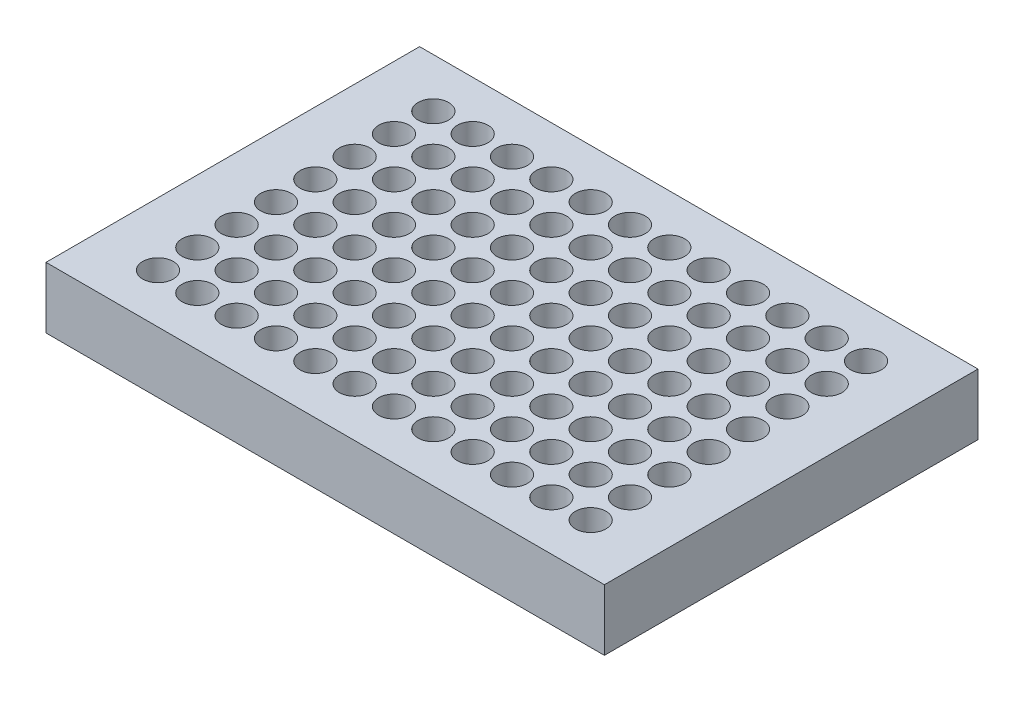
SolidWorks part; units mm, degrees
ref_plane "Front Plane" through (0, 0, 0) normal (0, 0, 1) x (1, 0, 0)
ref_plane "Top Plane" through (0, 0, 0) normal (0, 1, 0) x (1, 0, 0)
ref_plane "Right Plane" through (0, 0, 0) normal (1, 0, 0) x (0, 0, -1)
sketch "Sketch1" plane through (0, 0, 0) normal (0, 1, 0) x (1, 0, 0)
  line L0 (63.88, 85.48) -> (63.88, 0) construction
  line L1 (0, 0) -> (127.76, 0)
  line L2 (0, 0) -> (0, 85.48)
  line L3 (0, 85.48) -> (127.76, 85.48)
  line L4 (127.76, 0) -> (127.76, 85.48)
  line L5 (127.76, 42.74) -> (0, 42.74) construction
  circle A0 centre (59.38, 47.24) radius 3.5 construction
  circle A1 centre (14.38, 38.24) radius 3.5 construction
  circle A2 centre (23.38, 38.24) radius 3.5 construction
  circle A3 centre (32.38, 38.24) radius 3.5 construction
  circle A4 centre (50.38, 47.24) radius 3.5 construction
  circle A5 centre (41.38, 47.24) radius 3.5 construction
  circle A6 centre (32.38, 47.24) radius 3.5 construction
  circle A7 centre (23.38, 47.24) radius 3.5 construction
  circle A8 centre (14.38, 47.24) radius 3.5 construction
  circle A9 centre (41.38, 38.24) radius 3.5 construction
  circle A10 centre (50.38, 38.24) radius 3.5 construction
  circle A11 centre (59.38, 38.24) radius 3.5 construction
  circle A12 centre (68.38, 38.24) radius 3.5 construction
  circle A13 centre (77.38, 38.24) radius 3.5 construction
  circle A14 centre (86.38, 38.24) radius 3.5 construction
  circle A15 centre (113.38, 47.24) radius 3.5 construction
  circle A16 centre (104.38, 47.24) radius 3.5 construction
  circle A17 centre (95.38, 47.24) radius 3.5 construction
  circle A18 centre (86.38, 47.24) radius 3.5 construction
  circle A19 centre (77.38, 47.24) radius 3.5 construction
  circle A20 centre (95.38, 38.24) radius 3.5 construction
  circle A21 centre (104.38, 38.24) radius 3.5 construction
  circle A22 centre (113.38, 38.24) radius 3.5 construction
  circle A23 centre (68.38, 47.24) radius 3.5 construction
  circle A24 centre (59.38, 56.24) radius 3.5 construction
  circle A25 centre (50.38, 56.24) radius 3.5 construction
  circle A26 centre (41.38, 56.24) radius 3.5 construction
  circle A27 centre (32.38, 56.24) radius 3.5 construction
  circle A28 centre (23.38, 56.24) radius 3.5 construction
  circle A29 centre (14.38, 56.24) radius 3.5 construction
  circle A30 centre (113.38, 56.24) radius 3.5 construction
  circle A31 centre (104.38, 56.24) radius 3.5 construction
  circle A32 centre (95.38, 56.24) radius 3.5 construction
  circle A33 centre (86.38, 56.24) radius 3.5 construction
  circle A34 centre (77.38, 56.24) radius 3.5 construction
  circle A35 centre (68.38, 56.24) radius 3.5 construction
  circle A36 centre (59.38, 65.24) radius 3.5 construction
  circle A37 centre (50.38, 65.24) radius 3.5 construction
  circle A38 centre (41.38, 65.24) radius 3.5 construction
  circle A39 centre (32.38, 65.24) radius 3.5 construction
  circle A40 centre (23.38, 65.24) radius 3.5 construction
  circle A41 centre (14.38, 65.24) radius 3.5 construction
  circle A42 centre (113.38, 65.24) radius 3.5 construction
  circle A43 centre (104.38, 65.24) radius 3.5 construction
  circle A44 centre (95.38, 65.24) radius 3.5 construction
  circle A45 centre (86.38, 65.24) radius 3.5 construction
  circle A46 centre (77.38, 65.24) radius 3.5 construction
  circle A47 centre (68.38, 65.24) radius 3.5 construction
  circle A48 centre (59.38, 74.24) radius 3.5 construction
  circle A49 centre (50.38, 74.24) radius 3.5 construction
  circle A50 centre (41.38, 74.24) radius 3.5 construction
  circle A51 centre (32.38, 74.24) radius 3.5 construction
  circle A52 centre (23.38, 74.24) radius 3.5 construction
  circle A53 centre (14.38, 74.24) radius 3.5 construction
  circle A54 centre (113.38, 74.24) radius 3.5 construction
  circle A55 centre (104.38, 74.24) radius 3.5 construction
  circle A56 centre (95.38, 74.24) radius 3.5 construction
  circle A57 centre (86.38, 74.24) radius 3.5 construction
  circle A58 centre (77.38, 74.24) radius 3.5 construction
  circle A59 centre (68.38, 74.24) radius 3.5 construction
  circle A60 centre (14.38, 29.24) radius 3.5 construction
  circle A61 centre (23.38, 29.24) radius 3.5 construction
  circle A62 centre (32.38, 29.24) radius 3.5 construction
  circle A63 centre (41.38, 29.24) radius 3.5 construction
  circle A64 centre (50.38, 29.24) radius 3.5 construction
  circle A65 centre (59.38, 29.24) radius 3.5 construction
  circle A66 centre (68.38, 29.24) radius 3.5 construction
  circle A67 centre (77.38, 29.24) radius 3.5 construction
  circle A68 centre (86.38, 29.24) radius 3.5 construction
  circle A69 centre (95.38, 29.24) radius 3.5 construction
  circle A70 centre (104.38, 29.24) radius 3.5 construction
  circle A71 centre (113.38, 29.24) radius 3.5 construction
  circle A72 centre (14.38, 20.24) radius 3.5 construction
  circle A73 centre (23.38, 20.24) radius 3.5 construction
  circle A74 centre (32.38, 20.24) radius 3.5 construction
  circle A75 centre (41.38, 20.24) radius 3.5 construction
  circle A76 centre (50.38, 20.24) radius 3.5 construction
  circle A77 centre (59.38, 20.24) radius 3.5 construction
  circle A78 centre (68.38, 20.24) radius 3.5 construction
  circle A79 centre (77.38, 20.24) radius 3.5 construction
  circle A80 centre (86.38, 20.24) radius 3.5 construction
  circle A81 centre (95.38, 20.24) radius 3.5 construction
  circle A82 centre (104.38, 20.24) radius 3.5 construction
  circle A83 centre (113.38, 20.24) radius 3.5 construction
  circle A84 centre (14.38, 11.24) radius 3.5 construction
  circle A85 centre (23.38, 11.24) radius 3.5 construction
  circle A86 centre (32.38, 11.24) radius 3.5 construction
  circle A87 centre (41.38, 11.24) radius 3.5 construction
  circle A88 centre (50.38, 11.24) radius 3.5 construction
  circle A89 centre (59.38, 11.24) radius 3.5 construction
  circle A90 centre (68.38, 11.24) radius 3.5 construction
  circle A91 centre (77.38, 11.24) radius 3.5 construction
  circle A92 centre (86.38, 11.24) radius 3.5 construction
  circle A93 centre (95.38, 11.24) radius 3.5 construction
  circle A94 centre (104.38, 11.24) radius 3.5 construction
  circle A95 centre (113.38, 11.24) radius 3.5 construction
  dimension "D5" = 6
  dimension "D1" = 85.48
  dimension "D2" = 127.76
  dimension "D3" = 4
  dimension "D4" = 4
extrude "Boss-Extrude1" add sketch "Sketch1" along normal blind 14
sketch "Sketch6" plane through (0, 14, 0) normal (0, 1, 0) x (1, 0, 0)
  line L0 (63.88, 85.48) -> (63.88, 0) construction
  line L1 (0, 0) -> (127.76, 0) construction
  line L2 (0, 0) -> (0, 85.48) construction
  line L3 (0, 85.48) -> (127.76, 85.48) construction
  line L4 (127.76, 0) -> (127.76, 85.48) construction
  line L5 (127.76, 42.74) -> (0, 42.74) construction
  circle A0 centre (59.38, 47.24) radius 3.5
  circle A1 centre (14.38, 38.24) radius 3.5
  circle A2 centre (23.38, 38.24) radius 3.5
  circle A3 centre (32.38, 38.24) radius 3.5
  circle A4 centre (50.38, 47.24) radius 3.5
  circle A5 centre (41.38, 47.24) radius 3.5
  circle A6 centre (32.38, 47.24) radius 3.5
  circle A7 centre (23.38, 47.24) radius 3.5
  circle A8 centre (14.38, 47.24) radius 3.5
  circle A9 centre (41.38, 38.24) radius 3.5
  circle A10 centre (50.38, 38.24) radius 3.5
  circle A11 centre (59.38, 38.24) radius 3.5
  circle A12 centre (68.38, 38.24) radius 3.5
  circle A13 centre (77.38, 38.24) radius 3.5
  circle A14 centre (86.38, 38.24) radius 3.5
  circle A15 centre (113.38, 47.24) radius 3.5
  circle A16 centre (104.38, 47.24) radius 3.5
  circle A17 centre (95.38, 47.24) radius 3.5
  circle A18 centre (86.38, 47.24) radius 3.5
  circle A19 centre (77.38, 47.24) radius 3.5
  circle A20 centre (95.38, 38.24) radius 3.5
  circle A21 centre (104.38, 38.24) radius 3.5
  circle A22 centre (113.38, 38.24) radius 3.5
  circle A23 centre (68.38, 47.24) radius 3.5
  circle A24 centre (59.38, 56.24) radius 3.5
  circle A25 centre (50.38, 56.24) radius 3.5
  circle A26 centre (41.38, 56.24) radius 3.5
  circle A27 centre (32.38, 56.24) radius 3.5
  circle A28 centre (23.38, 56.24) radius 3.5
  circle A29 centre (14.38, 56.24) radius 3.5
  circle A30 centre (113.38, 56.24) radius 3.5
  circle A31 centre (104.38, 56.24) radius 3.5
  circle A32 centre (95.38, 56.24) radius 3.5
  circle A33 centre (86.38, 56.24) radius 3.5
  circle A34 centre (77.38, 56.24) radius 3.5
  circle A35 centre (68.38, 56.24) radius 3.5
  circle A36 centre (59.38, 65.24) radius 3.5
  circle A37 centre (50.38, 65.24) radius 3.5
  circle A38 centre (41.38, 65.24) radius 3.5
  circle A39 centre (32.38, 65.24) radius 3.5
  circle A40 centre (23.38, 65.24) radius 3.5
  circle A41 centre (14.38, 65.24) radius 3.5
  circle A42 centre (113.38, 65.24) radius 3.5
  circle A43 centre (104.38, 65.24) radius 3.5
  circle A44 centre (95.38, 65.24) radius 3.5
  circle A45 centre (86.38, 65.24) radius 3.5
  circle A46 centre (77.38, 65.24) radius 3.5
  circle A47 centre (68.38, 65.24) radius 3.5
  circle A48 centre (59.38, 74.24) radius 3.5
  circle A49 centre (50.38, 74.24) radius 3.5
  circle A50 centre (41.38, 74.24) radius 3.5
  circle A51 centre (32.38, 74.24) radius 3.5
  circle A52 centre (23.38, 74.24) radius 3.5
  circle A53 centre (14.38, 74.24) radius 3.5
  circle A54 centre (113.38, 74.24) radius 3.5
  circle A55 centre (104.38, 74.24) radius 3.5
  circle A56 centre (95.38, 74.24) radius 3.5
  circle A57 centre (86.38, 74.24) radius 3.5
  circle A58 centre (77.38, 74.24) radius 3.5
  circle A59 centre (68.38, 74.24) radius 3.5
  circle A60 centre (14.38, 29.24) radius 3.5
  circle A61 centre (23.38, 29.24) radius 3.5
  circle A62 centre (32.38, 29.24) radius 3.5
  circle A63 centre (41.38, 29.24) radius 3.5
  circle A64 centre (50.38, 29.24) radius 3.5
  circle A65 centre (59.38, 29.24) radius 3.5
  circle A66 centre (68.38, 29.24) radius 3.5
  circle A67 centre (77.38, 29.24) radius 3.5
  circle A68 centre (86.38, 29.24) radius 3.5
  circle A69 centre (95.38, 29.24) radius 3.5
  circle A70 centre (104.38, 29.24) radius 3.5
  circle A71 centre (113.38, 29.24) radius 3.5
  circle A72 centre (14.38, 20.24) radius 3.5
  circle A73 centre (23.38, 20.24) radius 3.5
  circle A74 centre (32.38, 20.24) radius 3.5
  circle A75 centre (41.38, 20.24) radius 3.5
  circle A76 centre (50.38, 20.24) radius 3.5
  circle A77 centre (59.38, 20.24) radius 3.5
  circle A78 centre (68.38, 20.24) radius 3.5
  circle A79 centre (77.38, 20.24) radius 3.5
  circle A80 centre (86.38, 20.24) radius 3.5
  circle A81 centre (95.38, 20.24) radius 3.5
  circle A82 centre (104.38, 20.24) radius 3.5
  circle A83 centre (113.38, 20.24) radius 3.5
  circle A84 centre (14.38, 11.24) radius 3.5
  circle A85 centre (23.38, 11.24) radius 3.5
  circle A86 centre (32.38, 11.24) radius 3.5
  circle A87 centre (41.38, 11.24) radius 3.5
  circle A88 centre (50.38, 11.24) radius 3.5
  circle A89 centre (59.38, 11.24) radius 3.5
  circle A90 centre (68.38, 11.24) radius 3.5
  circle A91 centre (77.38, 11.24) radius 3.5
  circle A92 centre (86.38, 11.24) radius 3.5
  circle A93 centre (95.38, 11.24) radius 3.5
  circle A94 centre (104.38, 11.24) radius 3.5
  circle A95 centre (113.38, 11.24) radius 3.5
  dimension "D5" = 6
  dimension "D1" = 85.48
  dimension "D2" = 127.76
  dimension "D3" = 4
  dimension "D4" = 4
extrude "Cut-Extrude1" cut sketch "Sketch6" against normal blind 8
